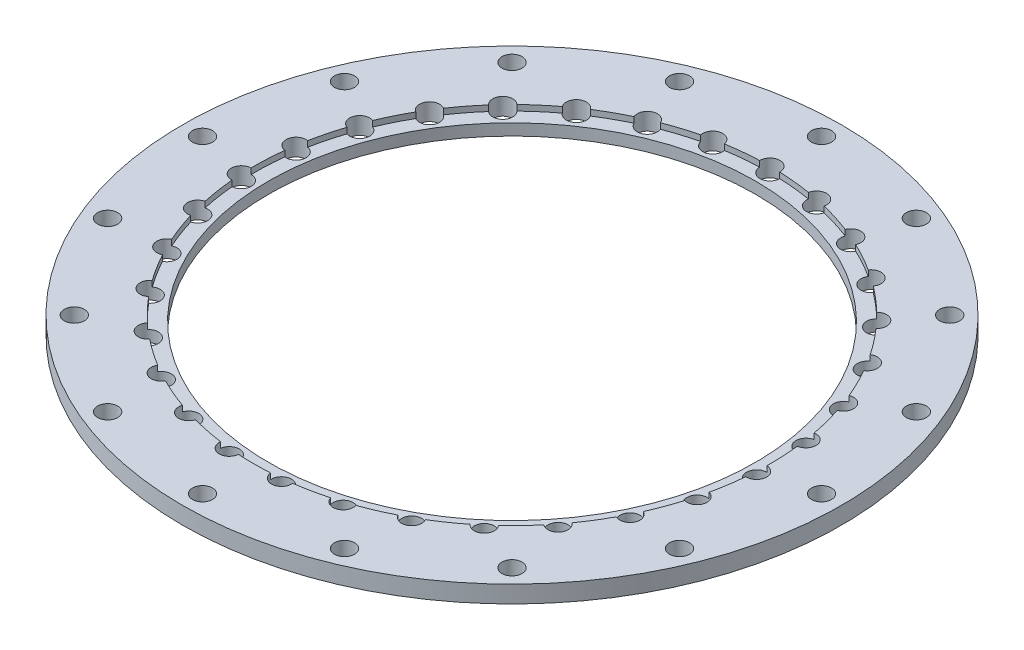
SolidWorks part; units mm, degrees
other "Markup1"
sketch "Sketch12" plane through (-57.5, 16, 57.5) normal (-0.5757, 0.7687, 0.2786) x (0.7628, 0.3823, 0.5216)
other "Markup2"
sketch "Sketch13" plane through (-57.5, 16, 57.5) normal (-0.5757, 0.7687, 0.2786) x (0.7628, 0.3823, 0.5216)
ref_plane "Front Plane" through (0, 0, 0) normal (0, 0, 1) x (1, 0, 0)
ref_plane "Top Plane" through (0, 0, 0) normal (0, 1, 0) x (1, 0, 0)
ref_plane "Right Plane" through (0, 0, 0) normal (1, 0, 0) x (0, 0, -1)
sketch "Sketch1" plane through (0, 0, 0) normal (0, 1, 0) x (1, 0, 0)
  line L0 (15.8389, 51.6249) -> (0, 0) construction
  line L1 (0, 0) -> (-4.5526, -44.7691) construction
  circle A0 centre (0, 0) radius 45
  circle A12 centre (0, 0) radius 57.5
  circle A13 centre (0, 0) radius 54 construction
  point P27 (0, 0)
  point P54 (0, 0)
  dimension "D1" = 90
  dimension "D4" = 115
  dimension "D5" = 108
  dimension "D8" = 11.25
extrude "Boss-Extrude1" add sketch "Sketch1" along normal blind 13
sketch "Sketch2" plane through (0, 0, 0) normal (0, -1, 0) x (1, 0, 0)
  circle A0 centre (0, 0) radius 57.5
  circle A1 centre (0, 0) radius 45
extrude "Boss-Extrude2" add sketch "Sketch2" along normal blind 1
sketch "Sketch3" plane through (0, -1, 0) normal (0, -1, 0) x (1, 0, 0)
  circle A0 centre (0, 0) radius 57.5
  circle A1 centre (0, 0) radius 42.5
  dimension "D1" = 85
extrude "Boss-Extrude3" add sketch "Sketch3" along normal blind 2
sketch "Sketch5" plane through (0, 13, 0) normal (0, 1, 0) x (1, 0, 0)
  circle A0 centre (0, 45) radius 3
  circle A1 centre (0, 0) radius 45 construction
  circle A2 centre (0, 0) radius 45 construction
  dimension "D1" = 6
extrude "Cut-Extrude2" cut sketch "Sketch5" against normal blind 13
fillet "Fillet4" radius 0.5 2 edges at (2.9983, 6.5, -44.9) (-2.9983, 6.5, -44.9)
sketch "Sketch10" plane through (0, 13, 0) normal (0, 1, 0) x (1, 0, 0)
  circle A0 centre (0, 0) radius 45
  circle A1 centre (0, 0) radius 57.5
extrude "Boss-Extrude4" add sketch "Sketch10" along normal blind 1
sketch "Sketch11" plane through (0, 14, 0) normal (0, 1, 0) x (1, 0, 0)
  circle A0 centre (0, 0) radius 42.5
  circle A1 centre (0, 0) radius 57.5
extrude "Boss-Extrude5" add sketch "Sketch11" along normal blind 2
sketch "Sketch7" plane through (0, 16, 0) normal (0, 1, 0) x (1, 0, 0)
  circle A0 centre (0, 45) radius 1.75
  arc A1 (3.4425, 44.8681) -> (-3.4425, 44.8681) centre (0, 0) ccw construction
  dimension "D1" = 3.5
extrude "Cut-Extrude3" cut sketch "Sketch7" against normal blind 23
pattern_circular "CirPattern3" count 31 over 360 about axis through (0, 0, 0) along (0, 1, 0) of "Cut-Extrude2", "Fillet4", "Cut-Extrude3"
sketch "Sketch4" plane through (0, 16, 0) normal (0, 1, 0) x (1, 0, 0)
  circle A0 centre (0, 0) radius 54 construction
  circle A1 centre (0, 54) radius 1.75
  circle A2 centre (20.6649, 49.8895) radius 1.75
  circle A3 centre (38.1838, 38.1838) radius 1.75
  circle A4 centre (49.8895, 20.6649) radius 1.75
  circle A5 centre (54, 0) radius 1.75
  circle A6 centre (49.8895, -20.6649) radius 1.75
  circle A7 centre (38.1838, -38.1838) radius 1.75
  circle A8 centre (20.6649, -49.8895) radius 1.75
  circle A9 centre (0, -54) radius 1.75
  circle A10 centre (-20.6649, -49.8895) radius 1.75
  circle A11 centre (-38.1838, -38.1838) radius 1.75
  circle A12 centre (-49.8895, -20.6649) radius 1.75
  circle A13 centre (-54, 0) radius 1.75
  circle A14 centre (-49.8895, 20.6649) radius 1.75
  circle A15 centre (-38.1838, 38.1838) radius 1.75
  circle A16 centre (-20.6649, 49.8895) radius 1.75
  circle A17 centre (0, 0) radius 45 construction
  point P38 (0, 0)
  point P102 (0, 0)
  dimension "D1" = 108
  dimension "D2" = 3.5
extrude "Cut-Extrude1" cut sketch "Sketch4" against normal blind 51
sketch "Sketch14" plane through (0, 0, 0) normal (0, 1, 0) x (1, 0, 0)
  circle A0 centre (0, 0) radius 84.7001
extrude "Cut-Extrude4" cut sketch "Sketch14" along normal blind 54
